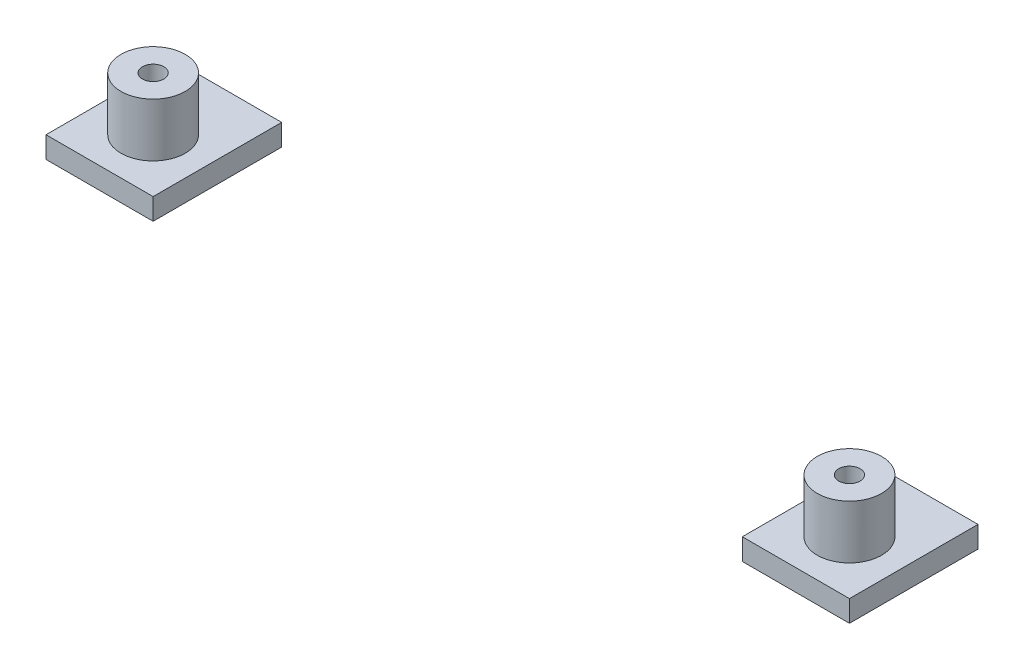
SolidWorks part; units mm, degrees
material "1060 Alloy"
ref_plane "Front Plane" through (0, 0, 0) normal (0, 0, 1) x (1, 0, 0)
ref_plane "Top Plane" through (0, 0, 0) normal (0, 1, 0) x (1, 0, 0)
ref_plane "Right Plane" through (0, 0, 0) normal (1, 0, 0) x (0, 0, -1)
sketch "Sketch1" plane through (0, 0, 0) normal (0, 0, 1) x (1, 0, 0)
  line L0 (-37.5, 0) -> (37.5, 0)
  line L1 (37.5, 2) -> (37.5, 0)
  line L2 (-37.5, 11) -> (-37.5, -4) construction
  line L3 (-37.5, 2) -> (-37.5, 0)
  line L5 (37.5, 2) -> (-37.5, 2)
  line L6 (0, 0) -> (0, 2) construction
  dimension "D1" = 2
extrude "Boss-Extrude1" add sketch "Sketch1" along normal up to surface (10 mm away)
sketch "Sketch2" plane through (0, 2, 0) normal (0, 1, 0) x (1, 0, 0)
  line L0 (0, 0) -> (0, -10) construction
  line L1 (37.5, -10) -> (37.5, 0) construction
  line L2 (32.5, -5) -> (32.5, -10) construction
  line L3 (37.5, -10) -> (-37.5, -10) construction
  line L5 (32.5, -5) -> (37.5, -5) construction
  line L6 (0, -10) -> (37.5, -10) construction
  line L7 (37.5, -10) -> (37.5, 0) construction
  line L8 (37.5, 0) -> (0, 0) construction
  circle A0 centre (32.5, -5) radius 1
  circle A1 centre (32.5, -5) radius 3
  circle A3 centre (-32.5, -5) radius 1
  circle A4 centre (-32.5, -5) radius 3
  dimension "D2" = 2
  dimension "D1" = 2
extrude "Boss-Extrude2" add sketch "Sketch2" along normal blind 5
sketch "Sketch3" plane through (0, 2, 0) normal (0, 1, 0) x (1, 0, 0)
  circle A0 centre (32.5, -5) radius 1
  circle A1 centre (-32.5, -5) radius 1
  circle A2 centre (32.5, -5) radius 1 construction
  circle A3 centre (-32.5, -5) radius 1 construction
extrude "Cut-Extrude1" cut sketch "Sketch3" against normal through all
sketch "Sketch4" plane through (0, 2, 0) normal (0, 1, 0) x (1, 0, 0)
  line L0 (0, -10) -> (0, 0) construction
  line L1 (37.5, -10) -> (-37.5, -10) construction
  line L2 (37.5, 0) -> (-37.5, 0) construction
  line L3 (32.5, -5) -> (32.5, -10) construction
  line L4 (-27.5, 0) -> (27.5, 0)
  line L5 (-27.5, 0) -> (-27.5, -10)
  line L6 (-27.5, -10) -> (27.5, -10)
  line L7 (27.5, 0) -> (27.5, -10)
  line L8 (-27.5, 0) -> (27.5, -10) construction
  line L9 (-27.5, -10) -> (27.5, 0) construction
  line L10 (32.5, -5) -> (37.5, -5) construction
  line L11 (37.5, -10) -> (37.5, 0) construction
  line L12 (32.5, -5) -> (27.5, -5) construction
  point P6 (0, -5)
extrude "Cut-Extrude2" cut sketch "Sketch4" against normal blind 10
sketch "Sketch5" plane through (0, 0, 0) normal (0, 0, -1) x (-1, 0, 0)
  line L4 (-37.5, 0) -> (-27.5, 0)
  line L5 (-27.5, 0) -> (-27.5, 2)
  line L6 (-27.5, 2) -> (-37.5, 2)
  line L7 (-37.5, 2) -> (-37.5, 0)
  line L8 (-37.5, 0) -> (-27.5, 0)
  line L9 (-27.5, 0) -> (-27.5, 2)
  line L10 (-27.5, 2) -> (-37.5, 2)
  line L11 (-37.5, 2) -> (-37.5, 0)
  dimension "D1" = 0
extrude "Boss-Extrude3" add sketch "Sketch5" along normal blind 2
sketch "Sketch6" plane through (0, 0, 0) normal (0, 0, -1) x (-1, 0, 0)
  line L4 (37.5, 2) -> (27.5, 2)
  line L5 (27.5, 2) -> (27.5, 0)
  line L6 (27.5, 0) -> (37.5, 0)
  line L7 (37.5, 0) -> (37.5, 2)
  line L8 (37.5, 2) -> (27.5, 2)
  line L9 (27.5, 2) -> (27.5, 0)
  line L10 (27.5, 0) -> (37.5, 0)
  line L11 (37.5, 0) -> (37.5, 2)
  dimension "D1" = 0
extrude "Boss-Extrude4" add sketch "Sketch6" along normal blind 2
